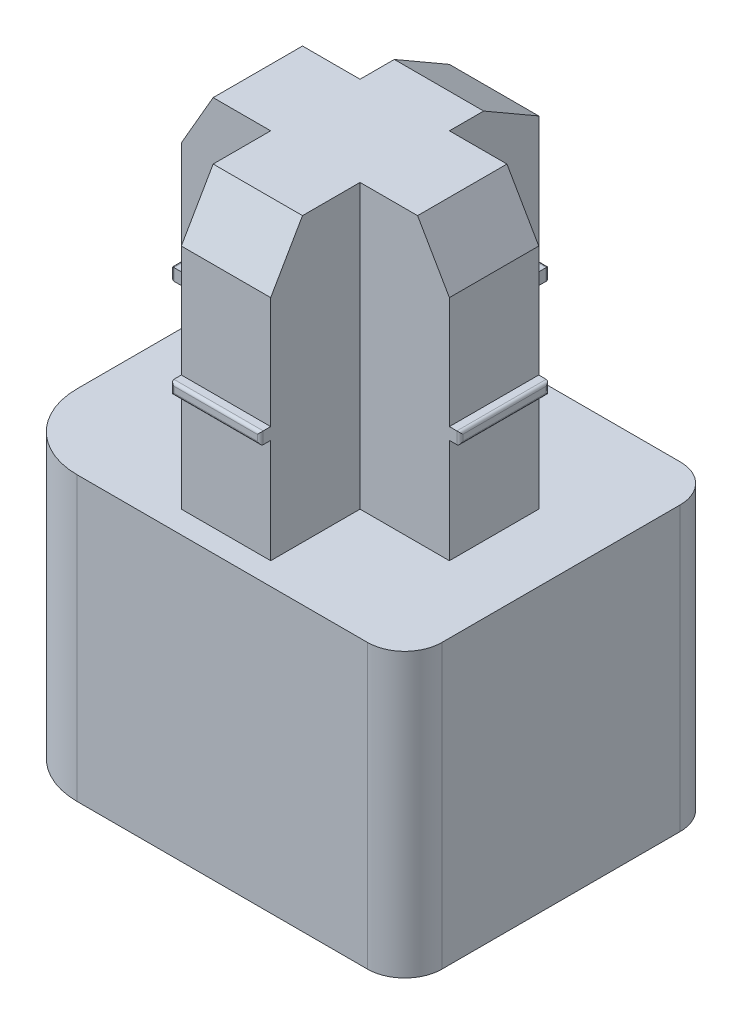
SolidWorks part; units mm, degrees
ref_plane "Front Plane" through (0, 0, 0) normal (0, 0, 1) x (1, 0, 0)
ref_plane "Top Plane" through (0, 0, 0) normal (0, 1, 0) x (1, 0, 0)
ref_plane "Right Plane" through (0, 0, 0) normal (1, 0, 0) x (0, 0, -1)
sketch "Sketch1" plane through (0, 0, 0) normal (0, 1, 0) x (1, 0, 0)
  line L1 (-3.429, 2.667) -> (3.429, 2.667)
  line L2 (-3.429, 2.667) -> (-3.429, -2.667)
  line L3 (-3.429, -2.667) -> (3.429, -2.667)
  line L4 (3.429, 2.667) -> (3.429, -2.667)
  line L5 (-3.429, 2.667) -> (3.429, -2.667) construction
  line L6 (-3.429, -2.667) -> (3.429, 2.667) construction
  point P0 (0, 0)
  dimension "D1" = 6.858
  dimension "D2" = 5.334
extrude "Boss-Extrude1" add sketch "Sketch1" along normal blind 4.826
sketch "Sketch2" plane through (0, 4.826, 0) normal (0, 1, 0) x (1, 0, 0)
  line L1 (-2.286, 0.762) -> (2.286, 0.762)
  line L2 (-2.286, 0.762) -> (-2.286, -0.762)
  line L3 (-2.286, -0.762) -> (2.286, -0.762)
  line L4 (2.286, 0.762) -> (2.286, -0.762)
  line L5 (-2.286, 0.762) -> (2.286, -0.762) construction
  line L6 (-2.286, -0.762) -> (2.286, 0.762) construction
  line L7 (-0.762, 2.286) -> (0.762, 2.286)
  line L8 (-0.762, 2.286) -> (-0.762, -2.286)
  line L9 (-0.762, -2.286) -> (0.762, -2.286)
  line L10 (0.762, 2.286) -> (0.762, -2.286)
  line L11 (-0.762, 2.286) -> (0.762, -2.286) construction
  line L12 (-0.762, -2.286) -> (0.762, 2.286) construction
  point P0 (0, 0)
  point P6 (0, 0)
  dimension "D1" = 1.524
  dimension "D2" = 1.524
  dimension "D3" = 4.572
  dimension "D4" = 4.572
extrude "Boss-Extrude2" add sketch "Sketch2" along normal blind 4.826 contours L10 L1 L8 L3 | L1 L10 L3 L4 | L10 L7 L8 L1 | L8 L1 L2 L3 | L10 L3 L8 L9
chamfer "Chamfer1" distance 0.9398 angle 30 4 edges at (2.286, 9.652, 0) (0, 9.652, -2.286) (-2.286, 9.652, 0) (0, 9.652, 2.286)
sketch "Sketch3" plane through (0, 9.652, 0) normal (0, 1, 0) x (1, 0, 0)
  line L1 (-2.4638, 0.762) -> (2.4638, 0.762)
  line L2 (-2.4638, 0.762) -> (-2.4638, -0.762)
  line L3 (-2.4638, -0.762) -> (2.4638, -0.762)
  line L4 (2.4638, 0.762) -> (2.4638, -0.762)
  line L5 (-2.4638, 0.762) -> (2.4638, -0.762) construction
  line L6 (-2.4638, -0.762) -> (2.4638, 0.762) construction
  line L7 (-0.762, -2.4638) -> (0.762, -2.4638)
  line L8 (-0.762, -2.4638) -> (-0.762, 2.4638)
  line L9 (-0.762, 2.4638) -> (0.762, 2.4638)
  line L10 (0.762, -2.4638) -> (0.762, 2.4638)
  line L11 (-0.762, -2.4638) -> (0.762, 2.4638) construction
  line L12 (-0.762, 2.4638) -> (0.762, -2.4638) construction
  point P0 (0, 0)
  point P6 (0, 0)
  line M5 (0.762, -0.762) -> (1.7434, -0.762)
  line M6 (1.7434, -0.762) -> (1.7434, 0.762)
  line M7 (1.7434, 0.762) -> (0.762, 0.762)
  line M8 (0.762, 0.762) -> (0.762, 1.3462)
  line M9 (0.762, 1.3462) -> (-0.762, 1.3462)
  line M10 (-0.762, 1.3462) -> (-0.762, 0.762)
  line M11 (-0.762, 0.762) -> (-1.7434, 0.762)
  line M12 (-1.7434, 0.762) -> (-1.7434, -0.762)
  line M13 (-1.7434, -0.762) -> (-0.762, -0.762)
  line M14 (-0.762, -0.762) -> (-0.762, -1.7434)
  line M15 (-0.762, -1.7434) -> (0.762, -1.7434)
  line M16 (0.762, -1.7434) -> (0.762, -0.762)
  dimension "D1" = 1.524
  dimension "D2" = 1.524
  dimension "D3" = 4.9276
  dimension "D4" = 4.9276
extrude "Boss-Extrude3" add sketch "Sketch3" along normal blind 0.2032 from offset 3.048 contours L4 L1 L3 M6 | L10 M5 M6 M7 | L10 L9 L8 M9 | L1 M10 M8 M9 | L3 L10 L1 L8 | L8 M13 M11 M12 | L2 L3 L1 M12 | L3 M14 M15 M16 | L7 L10 L8 M15 offset against normal yes
fillet "Fillet2" radius 0.0508 16 edges at (0.762, 6.7056, -2.4638) (0, 6.604, -2.4638) (0, 6.8072, -2.4638) (-0.762, 6.7056, -2.4638) (2.4638, 6.7056, 0.762) (2.4638, 6.7056, -0.762) (0.762, 6.7056, 2.4638) (-0.762, 6.7056, 2.4638) (-2.4638, 6.7056, -0.762) (-2.4638, 6.7056, 0.762) (-2.4638, 6.604, 0) (-2.4638, 6.8072, 0) (2.4638, 6.604, 0) (2.4638, 6.8072, 0) (0, 6.604, 2.4638) (0, 6.8072, 2.4638)
fillet "Fillet3" radius 0.635 3 edges at (-3.429, 2.413, -2.667) (3.429, 2.413, -2.667) (3.429, 2.413, 2.667)
fillet "Fillet6" radius 1.27 1 edges at (-3.429, 2.413, 2.667)
sketch "Sketch4" plane through (0, 0, 0) normal (0, -1, 0) x (1, 0, 0)
  line L1 (-1.6383, -1.6129) -> (1.6383, -1.6129)
  line L2 (-1.6383, -1.6129) -> (-1.6383, 1.6129)
  line L3 (-1.6383, 1.6129) -> (1.6383, 1.6129)
  line L4 (1.6383, -1.6129) -> (1.6383, 1.6129)
  line L5 (-1.6383, -1.6129) -> (1.6383, 1.6129) construction
  line L6 (-1.6383, 1.6129) -> (1.6383, -1.6129) construction
  point P0 (0, 0)
  dimension "D1" = 3.2258
  dimension "D2" = 3.2766
extrude "Cut-Extrude1" cut sketch "Sketch4" against normal blind 2.032
